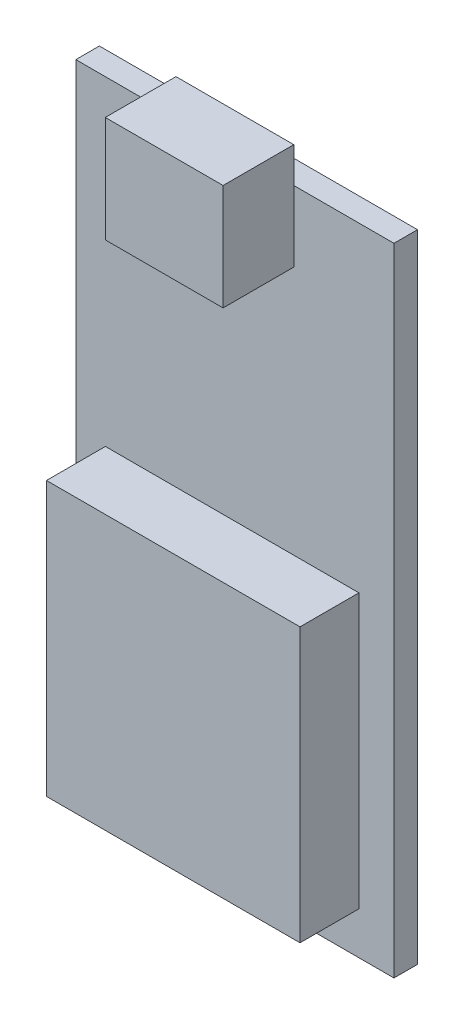
SolidWorks part; units mm, degrees
ref_plane "Front Plane" through (0, 0, 0) normal (0, 0, 1) x (1, 0, 0)
ref_plane "Top Plane" through (0, 0, 0) normal (0, 1, 0) x (1, 0, 0)
ref_plane "Right Plane" through (0, 0, 0) normal (1, 0, 0) x (0, 0, -1)
sketch "Sketch1" plane through (0, 0, 0) normal (0, 0, 1) x (1, 0, 0)
  line L1 (-94.1396, 536.0379) -> (-67.1396, 536.0379)
  line L2 (-94.1396, 536.0379) -> (-94.1396, 590.0379)
  line L3 (-94.1396, 590.0379) -> (-67.1396, 590.0379)
  line L4 (-67.1396, 536.0379) -> (-67.1396, 590.0379)
  dimension "D1" = 54
  dimension "D2" = 27
extrude "Boss-Extrude1" add sketch "Sketch1" along normal blind 2
sketch "Sketch2" plane through (0, 0, 2) normal (0, 0, 1) x (1, 0, 0)
  line L1 (-91.6278, 539.6381) -> (-70.1116, 539.6381)
  line L2 (-91.6278, 539.6381) -> (-91.6278, 562.862)
  line L3 (-91.6278, 562.862) -> (-70.1116, 562.862)
  line L4 (-70.1116, 539.6381) -> (-70.1116, 562.862)
extrude "Boss-Extrude2" add sketch "Sketch2" along normal blind 5
sketch "Sketch3" plane through (0, 0, 2) normal (0, 0, 1) x (1, 0, 0)
  line L0 (-80.6396, 590.0379) -> (-80.6396, 535.9898) construction
  line L1 (-85.6396, 593.0379) -> (-75.6396, 593.0379)
  line L2 (-85.6396, 593.0379) -> (-85.6396, 584.0379)
  line L3 (-85.6396, 584.0379) -> (-75.6396, 584.0379)
  line L4 (-75.6396, 593.0379) -> (-75.6396, 584.0379)
  line L5 (-67.1396, 590.0379) -> (-94.1396, 590.0379) construction
  point P8 (0, 0)
  dimension "D1" = 5
  dimension "D2" = 5
  dimension "D3" = 6
  dimension "D4" = 3
extrude "Boss-Extrude3" add sketch "Sketch3" along normal blind 6
